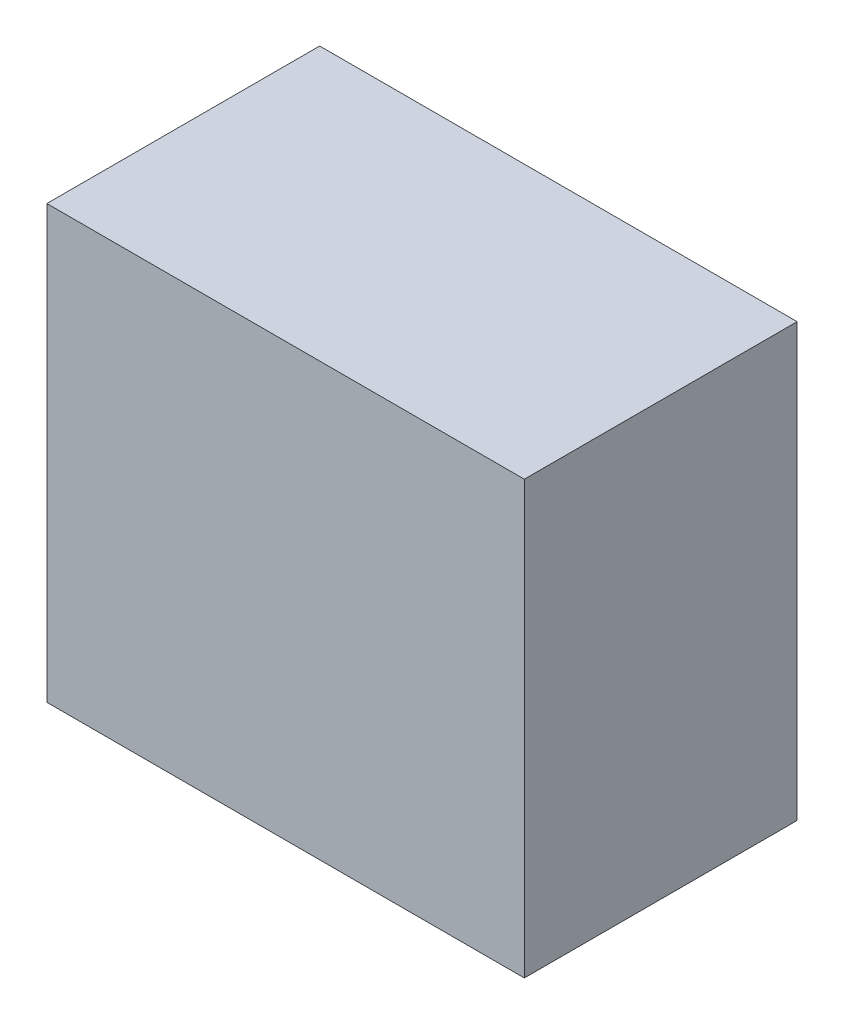
SolidWorks part; units mm, degrees
ref_plane "前视基准面" through (0, 0, 0) normal (0, 0, 1) x (1, 0, 0)
ref_plane "上视基准面" through (0, 0, 0) normal (0, 1, 0) x (1, 0, 0)
ref_plane "右视基准面" through (0, 0, 0) normal (1, 0, 0) x (0, 0, -1)
other "Configuration Table"
sketch "草图1" plane through (0, 0, 0) normal (0, 0, 1) x (1, 0, 0)
  line L1 (-21, -19) -> (21, -19)
  line L2 (-21, -19) -> (-21, 19)
  line L3 (-21, 19) -> (21, 19)
  line L4 (21, -19) -> (21, 19)
  line L5 (-21, -19) -> (21, 19) construction
  line L6 (-21, 19) -> (21, -19) construction
  point P0 (0, 0)
extrude "凸台-拉伸1" add sketch "草图1" along normal blind 24
